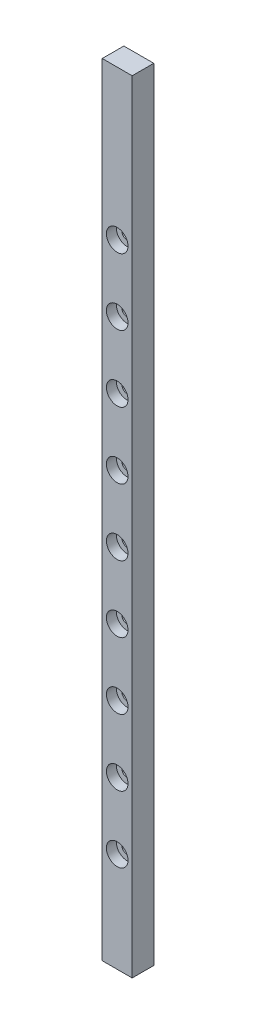
SolidWorks part; units mm, degrees
material "合金钢"
ref_plane "前视基准面" through (0, 0, 0) normal (0, 0, 1) x (1, 0, 0)
ref_plane "上视基准面" through (0, 0, 0) normal (0, 1, 0) x (1, 0, 0)
ref_plane "右视基准面" through (0, 0, 0) normal (1, 0, 0) x (0, 0, -1)
sketch "草图1" plane through (0, 0, 0) normal (0, 0, 1) x (1, 0, 0)
  line L1 (-4.5, 125) -> (4.5, 125)
  line L2 (-4.5, 125) -> (-4.5, -125)
  line L3 (-4.5, -125) -> (4.5, -125)
  line L4 (4.5, 125) -> (4.5, -125)
  line L5 (-4.5, 125) -> (4.5, -125) construction
  line L6 (-4.5, -125) -> (4.5, 125) construction
  point P0 (0, 0)
  dimension "D1" = 9
  dimension "D2" = 250
extrude "凸台-拉伸1" add sketch "草图1" along normal blind 6.5
ref_plane "基准面1" through (0, 0, 6.5) normal (0, 0, 1) x (1, 0, 0)
sketch "草图2" plane through (0, 0, 6.5) normal (0, 0, 1) x (1, 0, 0)
  circle A0 centre (0, 0) radius 1.6
  circle A1 centre (0, 20) radius 1.6
  circle A2 centre (0, 40) radius 1.6
  circle A3 centre (0, 60) radius 1.6
  circle A4 centre (0, 80) radius 1.6
  circle A5 centre (0, -20) radius 1.6
  circle A6 centre (0, -40) radius 1.6
  circle A7 centre (0, -60) radius 1.6
  circle A8 centre (0, -80) radius 1.6
  dimension "D1" = 3.2
  dimension "D2" = 5
  dimension "D3" = 5
extrude "切除-拉伸1" cut sketch "草图2" against normal through all
sketch "草图3" plane through (0, 0, 6.5) normal (0, 0, 1) x (1, 0, 0)
  circle A0 centre (0, 80) radius 3.25
  circle A1 centre (0, 60) radius 3.25
  circle A2 centre (0, 40) radius 3.25
  circle A3 centre (0, 20) radius 3.25
  circle A4 centre (0, 0) radius 3.25
  circle A5 centre (0, -20) radius 3.25
  circle A6 centre (0, -40) radius 3.25
  circle A7 centre (0, -60) radius 3.25
  circle A8 centre (0, -80) radius 3.25
  dimension "D1" = 6.5
  dimension "D2" = 9
extrude "切除-拉伸2" cut sketch "草图3" against normal blind 3
sketch "草图4" plane through (-4.5, 0, 0) normal (-1, 0, 0) x (0, 0, 1)
  line L0 (6.5, -4.95) -> (6.5, 4.95) construction
  line L1 (0, -125) -> (6.5, -125)
  line L2 (0, -125) -> (0, -110)
  line L3 (0, -110) -> (6.5, -110)
  line L4 (6.5, -125) -> (6.5, -110)
  dimension "D1" = 15
extrude "切除-拉伸3" cut sketch "草图4" against normal blind 10
